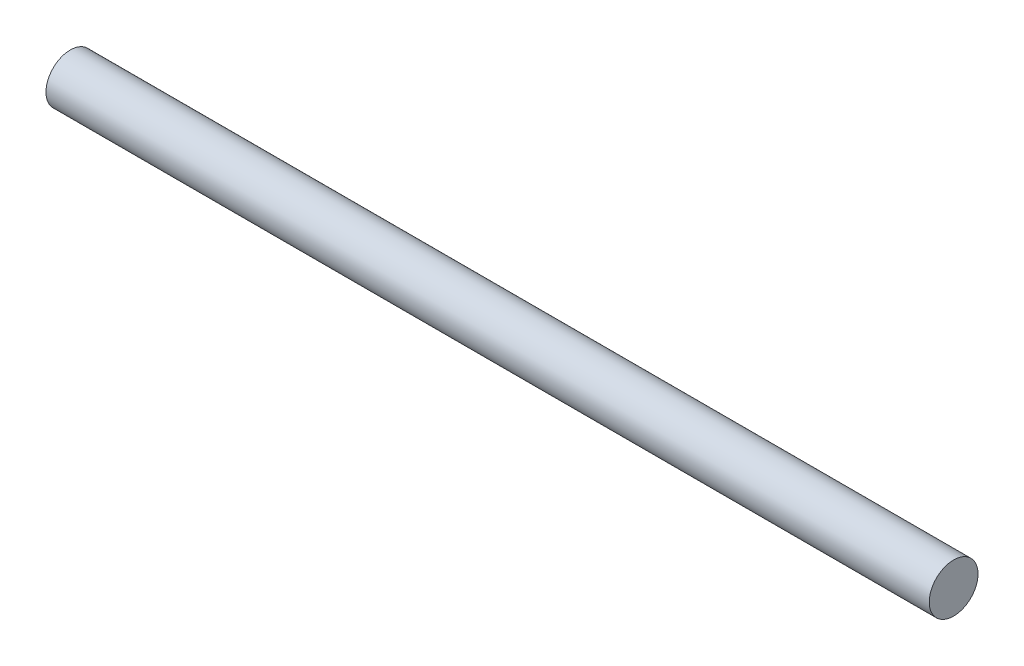
SolidWorks part; units mm, degrees
ref_plane "前视基准面" through (0, 0, 0) normal (0, 0, 1) x (1, 0, 0)
ref_plane "上视基准面" through (0, 0, 0) normal (0, 1, 0) x (1, 0, 0)
ref_plane "右视基准面" through (0, 0, 0) normal (1, 0, 0) x (0, 0, -1)
other "Configuration Table"
sketch "草图1" plane through (0, 0, 0) normal (1, 0, 0) x (0, 0, -1)
  circle A0 centre (0, 0) radius 4
  dimension "D1" = 8
extrude "凸台-拉伸1" add sketch "草图1" along normal blind 145
